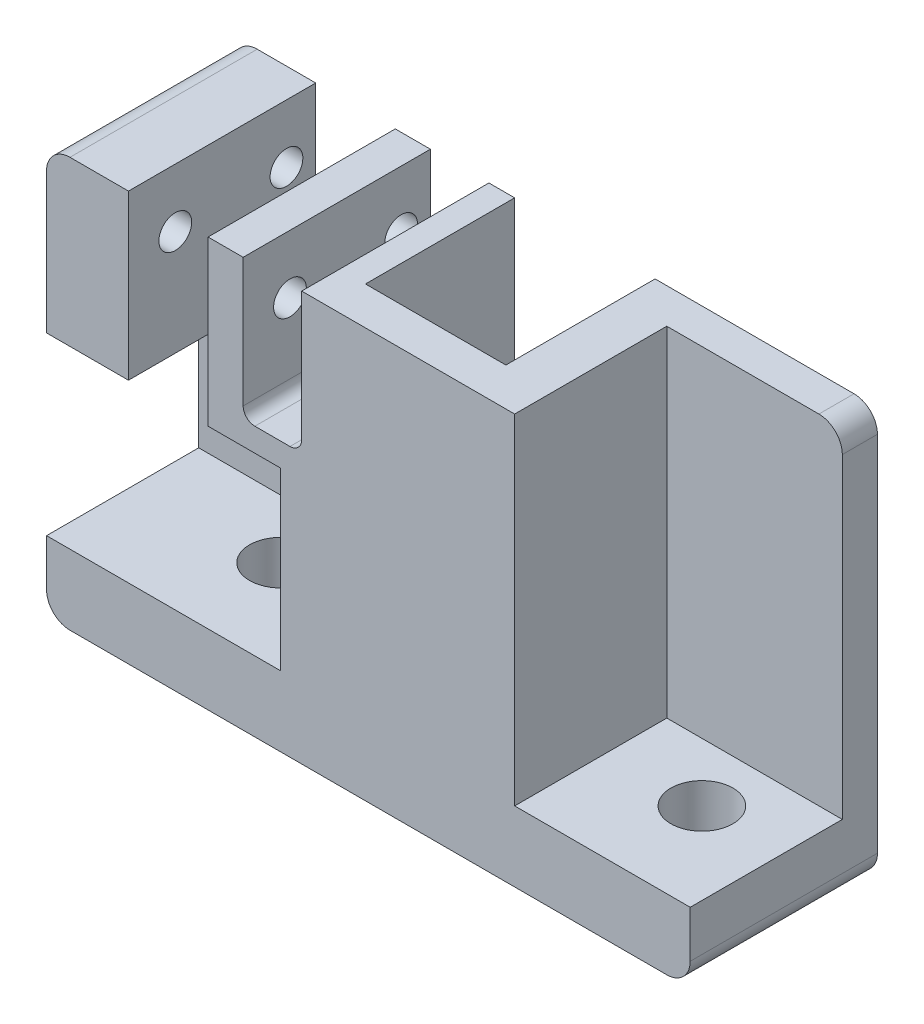
SolidWorks part; units mm, degrees
material "PLA"
ref_plane "前视基准面" through (0, 0, 0) normal (0, 0, 1) x (1, 0, 0)
ref_plane "上视基准面" through (0, 0, 0) normal (0, 1, 0) x (1, 0, 0)
ref_plane "右视基准面" through (0, 0, 0) normal (1, 0, 0) x (0, 0, -1)
other "Configuration Table"
sketch "草图1" plane through (0, 0, 0) normal (0, 0, 1) x (1, 0, 0)
  line L1 (-55, 35) -> (0, 35)
  line L2 (-55, 35) -> (-55, 0)
  line L3 (-55, 0) -> (0, 0)
  line L4 (0, 35) -> (0, 0)
  circle A2 centre (-52.5, 30) radius 1.15 construction
  circle A3 centre (-52.5, 23.5) radius 1.15 construction
  dimension "D2" = 35
  dimension "D4" = 2.5
  dimension "D7" = 2.3
  dimension "D8" = 6.5
  dimension "D9" = 5
  dimension "D10" = 52.5
  dimension "D3" = 55
extrude "凸台-拉伸1" add sketch "草图1" along normal blind 16
sketch "草图3" plane through (0, 0, 0) normal (0, -1, 0) x (1, 0, 0)
  line L0 (-55, 0) -> (0, 0) construction
  line L1 (0, 16) -> (0, 0) construction
  circle A0 centre (-43, 8) radius 2.65
  circle A1 centre (-7, 8) radius 2.65
  dimension "D1" = 36
  dimension "D2" = 5.3
  dimension "D3" = 8
  dimension "D4" = 7
extrude "切除-拉伸2" cut sketch "草图3" against normal blind 13
sketch "草图4" plane through (0, 0, 0) normal (0, -1, 0) x (1, 0, 0)
  line L0 (-31, 12.75) -> (-31, 0)
  line L2 (-31, 0) -> (-19, 0)
  line L3 (-19, 0) -> (-19, 12.75)
  line L4 (-25, 8) -> (-25, 23.0019) construction
  line L5 (-19, 12.75) -> (-31, 12.75)
  line L6 (-55, 0) -> (0, 0) construction
  line L7 (-7, 8) -> (-43, 8) construction
  circle A0 centre (-25, 8) radius 4.75 construction
  circle A1 centre (-7, 8) radius 2.65 construction
  circle A2 centre (-7, 8) radius 2.65 construction
  dimension "D1" = 9.5
  dimension "D2" = 12
extrude "切除-拉伸3" cut sketch "草图4" against normal through all
sketch "草图2" plane through (0, 0, 16) normal (0, 0, 1) x (1, 0, 0)
  line L0 (-37, 35) -> (-37, 0)
  line L1 (-12, 35) -> (-12, 0)
  line L2 (-37, 35) -> (-49, 35)
  line L3 (0, 35) -> (-55, 35) construction
  line L4 (0, 0) -> (0, 35)
  line L5 (0, 35) -> (-55, 35)
  line L6 (-55, 35) -> (-55, 0)
  line L7 (-55, 0) -> (0, 0)
  line L8 (0, 0) -> (0, 35)
  line L9 (0, 35) -> (-12, 35)
  line L12 (-49, 35) -> (-49, 0)
  line L13 (-49, 0) -> (-37, 0)
  line L14 (-49, 0) -> (-37, 0)
  line L15 (-12, 0) -> (0, 0)
  line M12 (0, 0) -> (0, 35)
  line M14 (0, 35) -> (-55, 35)
  line M31 (-55, 0) -> (0, 0)
  dimension "D2" = 37
  dimension "D3" = 12
  dimension "D4" = 12
  dimension "D1" = 0
extrude "切除-拉伸4" [suppressed] cut sketch "草图2" against normal blind 4 contours L12 L0 M14 M31 | L1 M14 M31 M12
sketch "草图5" [suppressed] plane through (0, 0, 12) normal (0, 0, 1) x (1, 0, 0)
  line L0 (-37, 43) -> (-37, 0) construction
  line L1 (-49, 43) -> (-37, 43)
  line L2 (-49, 43) -> (-49, 7)
  line L3 (-49, 7) -> (-37, 7)
  line L4 (-37, 43) -> (-37, 7)
  line L5 (0, 0) -> (0, 43) construction
  line L6 (-12, 43) -> (0, 43)
  line L7 (-12, 43) -> (-12, 7)
  line L8 (-12, 7) -> (0, 7)
  line L9 (0, 43) -> (0, 7)
  line L10 (-12, 43) -> (-12, 0) construction
  dimension "D1" = 36
extrude "切除-拉伸5" [suppressed] cut sketch "草图5" against normal blind 9
fillet "圆角1" radius 2 4 edges at (0, 35, 8) (-55, 35, 8) (0, 0, 8) (-55, 0, 8)
sketch "草图6" [suppressed] plane through (0, 0, 16) normal (0, 0, 1) x (1, 0, 0)
  line L0 (-49, 0) -> (-49, 43)
  line L1 (-53, 0) -> (-49, 0) construction
  line L2 (-49, 43) -> (-53, 43) construction
  line L3 (-53, 43) -> (-49, 43)
  line L4 (-49, 43) -> (-53, 43)
  line L5 (-55, 41) -> (-55, 2)
  line L6 (-53, 0) -> (-49, 0)
  line L7 (-49, 0) -> (-49, 43)
  line L9 (-55, 41) -> (-55, 2)
  line L12 (-49, 0) -> (-53, 0)
  line L13 (-37, 43) -> (-37, 0) construction
  arc A2 (-53, 43) -> (-55, 41) centre (-53, 41) ccw
  arc A3 (-55, 2) -> (-53, 0) centre (-53, 2) ccw
  arc A4 (-53, 43) -> (-55, 41) centre (-53, 41) ccw
  arc A5 (-55, 2) -> (-53, 0) centre (-53, 2) ccw
  dimension "D2" = 12
  dimension "D1" = 0
extrude "切除-拉伸6" [suppressed] cut sketch "草图6" against normal through all
fillet "圆角2" [suppressed] radius 2
sketch "草图8" [suppressed] plane through (0, 43, 0) normal (0, 1, 0) x (1, 0, 0)
  line L0 (-12, -16) -> (-37, -16) construction
  line L1 (-37, -16) -> (-27.65, -16)
  line L2 (-37, -16) -> (-37, -29)
  line L3 (-37, -29) -> (-27.65, -29)
  line L4 (-27.65, -16) -> (-27.65, -29)
  line L5 (-24.5, -16) -> (-24.5, -34.5504) construction
  line L6 (-21.35, -16) -> (-21.35, -29)
  line L7 (-12, -29) -> (-21.35, -29)
  line L8 (-12, -16) -> (-12, -29)
  line L9 (-12, -16) -> (-21.35, -16)
  dimension "D1" = 6.3
  dimension "D2" = 13
extrude "凸台-拉伸2" [suppressed] add sketch "草图8" against normal blind 6
sketch "草图9" [suppressed] plane through (-12, 0, 0) normal (1, 0, 0) x (0, 0, -1)
  line L0 (-16, 37) -> (-16, 0) construction
  line L1 (-29, 40) -> (-37.2325, 40) construction
  line L2 (-29, 37) -> (-29, 43) construction
  circle A0 centre (-16, 40) radius 1.15
  circle A1 centre (-22.5, 40) radius 1.15
  dimension "D1" = 2.3
  dimension "D2" = 0
  dimension "D3" = 6.5
extrude "切除-拉伸7" [suppressed] cut sketch "草图9" against normal through all
sketch "草图10" [suppressed] plane through (0, 43, 0) normal (0, 1, 0) x (1, 0, 0)
  line L0 (-19, -12.75) -> (-31, -12.75) construction
  line L1 (-27.65, -16) -> (-21.35, -16)
  line L2 (-27.65, -16) -> (-27.65, -12.75)
  line L3 (-27.65, -12.75) -> (-21.35, -12.75)
  line L4 (-21.35, -16) -> (-21.35, -12.75)
extrude "切除-拉伸8" [suppressed] cut sketch "草图10" against normal blind 7
sketch "草图11" plane through (-55, 0, 0) normal (-1, 0, 0) x (0, 0, 1)
  line L0 (16, 33) -> (16, 2) construction
  line L1 (16, 0) -> (0, 0) construction
  circle A0 centre (12, 30) radius 1.4
  circle A1 centre (2.5, 30) radius 1.4
  dimension "D1" = 9.5
  dimension "D2" = 2.8
  dimension "D4" = 30
  dimension "D3" = 4
extrude "切除-拉伸9" cut sketch "草图11" against normal blind 18 and the other way through all
sketch "草图12" plane through (0, 0, 16) normal (0, 0, 1) x (1, 0, 0)
  line L0 (-2, 35) -> (-53, 35) construction
  line L1 (-48, 35) -> (-41.2, 35)
  line L2 (-48, 35) -> (-48, 19)
  line L3 (-48, 19) -> (-41.2, 19)
  line L4 (-41.2, 35) -> (-41.2, 19)
  line L5 (-55, 33) -> (-55, 2) construction
  dimension "D1" = 6.8
  dimension "D2" = 7
  dimension "D3" = 16
extrude "切除-拉伸10" cut sketch "草图12" against normal through all
sketch "草图13" plane through (0, 0, 16) normal (0, 0, 1) x (1, 0, 0)
  line L0 (0, 2) -> (0, 33) construction
  line L1 (0, 6) -> (-15, 6)
  line L2 (0, 6) -> (0, 21)
  line L3 (0, 21) -> (-15, 21)
  line L4 (-15, 6) -> (-15, 21)
  line L6 (-53, 0) -> (-2, 0) construction
  line L7 (-27.5, 0) -> (-27.5, 43.3744) construction
  line L8 (-35, 6) -> (-35, 21)
  line L9 (-55, 21) -> (-35, 21)
  line L10 (-55, 6) -> (-55, 21)
  line L11 (-55, 6) -> (-35, 6)
  point P6 (0, 0)
  dimension "D1" = 15
  dimension "D2" = 6
  dimension "D3" = 15
  dimension "D4" = 20
extrude "切除-拉伸12" cut sketch "草图13" against normal blind 13
sketch "草图15" plane through (0, 0, 16) normal (0, 0, 1) x (1, 0, 0)
  line L1 (-15, 21) -> (5.5473, 21)
  line L2 (-15, 21) -> (-15, 39.9529)
  line L3 (-15, 39.9529) -> (5.5473, 39.9529)
  line L4 (5.5473, 21) -> (5.5473, 39.9529)
extrude "切除-拉伸13" cut sketch "草图15" against normal blind 13
sketch "草图16" plane through (0, 35, 0) normal (0, 1, 0) x (1, 0, 0)
  line L0 (-31, 0) -> (-41.2, 0) construction
  line L1 (-38.2, 0) -> (-33.2, 0)
  line L2 (-38.2, 0) -> (-38.2, -16)
  line L3 (-38.2, -16) -> (-33.2, -16)
  line L4 (-33.2, 0) -> (-33.2, -16)
  line L5 (-15, -16) -> (-41.2, -16) construction
  line L6 (-41.2, 0) -> (-41.2, -16) construction
  dimension "D1" = 3
  dimension "D2" = 5
extrude "切除-拉伸14" cut sketch "草图16" against normal blind 12
fillet "圆角3" radius 1 4 edges at (-38.2, 23, 8) (-33.2, 23, 8) (-48, 19, 1.5) (-41.2, 19, 1.5)
